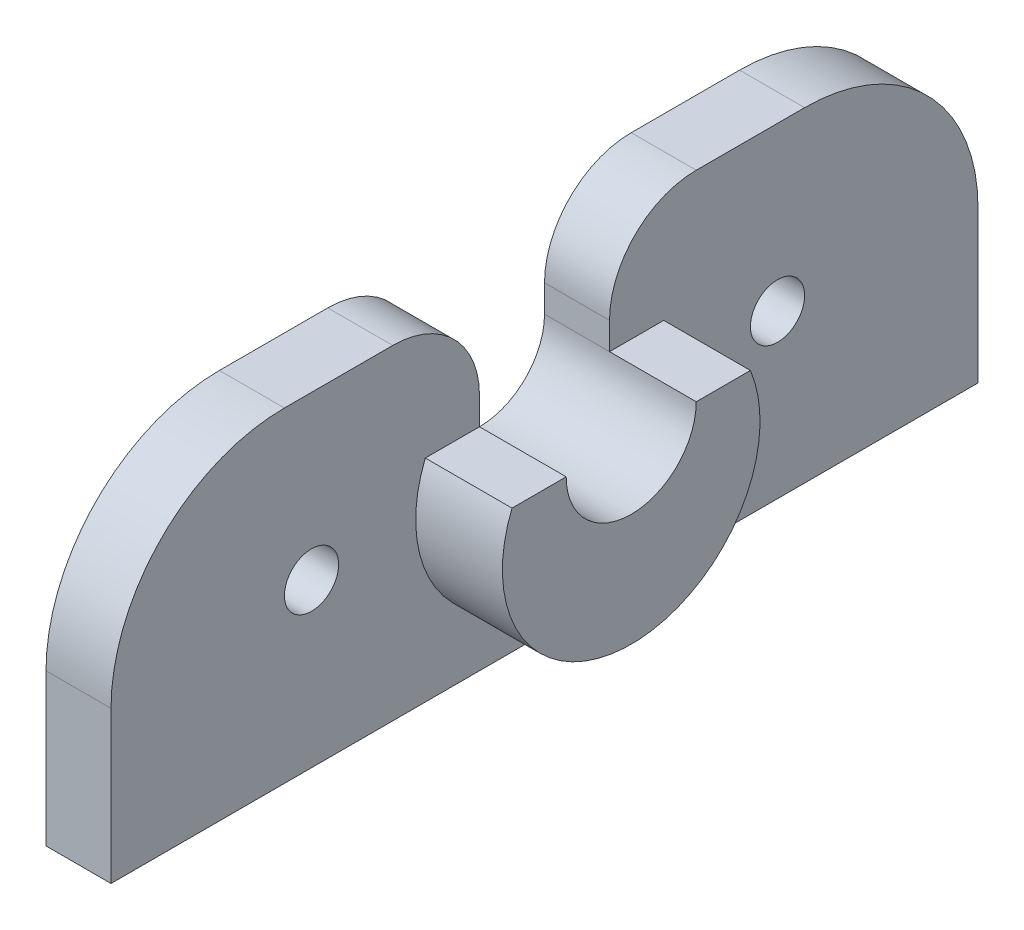
SolidWorks part; units mm, degrees
ref_plane "Front Plane" through (0, 0, 0) normal (0, 0, 1) x (1, 0, 0)
ref_plane "Top Plane" through (0, 0, 0) normal (0, 1, 0) x (1, 0, 0)
ref_plane "Right Plane" through (0, 0, 0) normal (1, 0, 0) x (0, 0, -1)
sketch "Sketch1" plane through (0, 0, 0) normal (1, 0, 0) x (0, 0, -1)
  line L1 (20, -7.5) -> (-20, -7.5)
  line L2 (20, -7.5) -> (20, 7.5)
  line L3 (20, 7.5) -> (-20, 7.5)
  line L4 (-20, -7.5) -> (-20, 7.5)
  line L5 (20, -7.5) -> (-20, 7.5) construction
  line L6 (20, 7.5) -> (-20, -7.5) construction
  point P0 (0, 0)
  dimension "D1" = 40
  dimension "D2" = 15
extrude "Boss-Extrude1" add sketch "Sketch1" along normal blind 3
sketch "Sketch2" plane through (3, 0, 0) normal (1, 0, 0) x (0, 0, -1)
  line L0 (-3, 2.25) -> (-3, 7.5)
  line L1 (20, 7.5) -> (-20, 7.5) construction
  line L2 (3, 2.25) -> (3, 7.5)
  line L3 (-20, -7.5) -> (20, -7.5) construction
  line L4 (3, 7.5) -> (-3, 7.5)
  circle A0 centre (-10.75, 0) radius 1.25
  arc A8 (-3, 2.25) -> (3, 2.25) centre (0, 2.25) ccw
  dimension "D3" = 2.5
  dimension "D4" = 6
  dimension "D5" = 10.75
  dimension "D2" = 5.25
  dimension "D1" = 7.5
extrude "Cut-Extrude1" cut sketch "Sketch2" against normal blind 5
mirror "Mirror1" about plane through (0, 0, 0) normal (0, 0, 1) of "Cut-Extrude1"
fillet "Fillet1" radius 8 2 edges at (1.5, 7.5, -20) (1.5, 7.5, 20)
sketch "Sketch3" plane through (3, 0, 0) normal (1, 0, 0) x (0, 0, -1)
  line L3 (-3, 2.25) -> (-5.5, 2.25)
  line L4 (3, 2.25) -> (5.5, 2.25)
  arc A2 (-5.5, 2.25) -> (5.5, 2.25) centre (0, 0) ccw
  arc A3 (-3, 2.25) -> (3, 2.25) centre (0, 2.25) ccw
  dimension "D1" = 2.5
  dimension "D2" = 3
extrude "Boss-Extrude2" add sketch "Sketch3" along normal blind 4
fillet "Fillet2" radius 4 2 edges at (1.5, 7.5, -3) (1.5, 7.5, 3)
